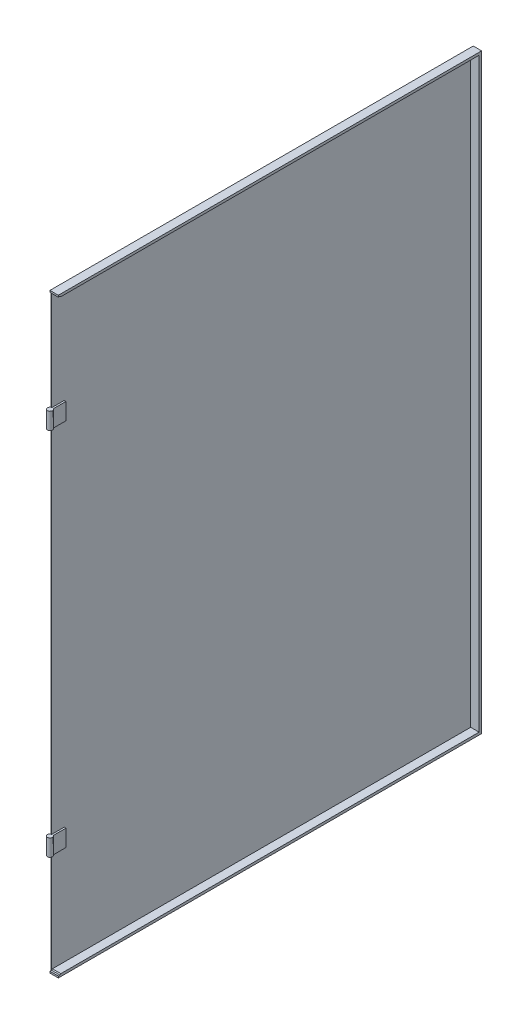
SolidWorks part; units mm, degrees
material "Acero inoxidable al cromo"
ref_plane "Alzado" through (0, 0, 0) normal (0, 0, 1) x (1, 0, 0)
ref_plane "Planta" through (0, 0, 0) normal (0, 1, 0) x (1, 0, 0)
ref_plane "Vista lateral" through (0, 0, 0) normal (1, 0, 0) x (0, 0, -1)
sketch "Croquis1" plane through (0, 0, 0) normal (0, 0, 1) x (1, 0, 0)
  line L1 (-250, -350) -> (250, -350)
  line L2 (-250, -350) -> (-250, 350)
  line L3 (-250, 350) -> (250, 350)
  line L4 (250, -350) -> (250, 350)
  line L5 (-250, -350) -> (250, 350) construction
  line L6 (-250, 350) -> (250, -350) construction
  point P0 (0, 0)
  dimension "D1" = 700
  dimension "D2" = 500
extrude "Saliente-Extruir1" add sketch "Croquis1" along normal blind 500
shell "Vaciado1" thickness 1
sketch "Croquis2" plane through (-249, 0, 0) normal (1, 0, 0) x (0, 0, -1)
  line L0 (-500, 349) -> (-500, -349) construction
  line L1 (-500, 230) -> (-485, 230)
  line L2 (-500, 230) -> (-500, 210)
  line L3 (-500, 210) -> (-485, 210)
  line L4 (-485, 230) -> (-485, 210)
  line L5 (-500, 350) -> (0, 350) construction
  line L6 (-500, -210) -> (-485, -210)
  line L7 (-500, -210) -> (-500, -230)
  line L8 (-500, -230) -> (-485, -230)
  line L9 (-485, -210) -> (-485, -230)
  line L10 (-500, -350) -> (0, -350) construction
  dimension "D1" = 20
  dimension "D2" = 15
  dimension "D3" = 20
  dimension "D4" = 15
  dimension "D5" = 120
  dimension "D6" = 120
extrude "Saliente-Extruir2" add sketch "Croquis2" along normal blind 2
sketch "Croquis3" plane through (0, -230, 0) normal (0, -1, 0) x (1, 0, 0)
  line L0 (-250, 500) -> (-250, 0) construction
  line L1 (-250, 500) -> (250, 500) construction
  circle A0 centre (-248.5, 502.5) radius 3
  dimension "D1" = 6
  dimension "D2" = 1.5
  dimension "D3" = 2.5
extrude "Saliente-Extruir3" add sketch "Croquis3" against normal up to vertex
sketch "Croquis4" plane through (0, 210, 0) normal (0, -1, 0) x (1, 0, 0)
  line L0 (-250, 499.9019) -> (-247, 499.9019)
  arc A0 (-247, 499.9019) -> (-250, 499.9019) centre (-248.5, 502.5) ccw construction
  arc A1 (-247, 499.9019) -> (-250, 499.9019) centre (-248.5, 502.5) ccw
extrude "Saliente-Extruir4" add sketch "Croquis4" against normal up to vertex contours A1 L0
sketch "Croquis5" plane through (-249, 0, 0) normal (1, 0, 0) x (0, 0, -1)
  line L12 (-485, -210) -> (-485, -230)
  line L13 (-485, -230) -> (-500, -230)
  line L14 (-500, -230) -> (-500, -349)
  line L15 (-500, -349) -> (-1, -349)
  line L16 (-1, -349) -> (-1, 349)
  line L17 (-1, 349) -> (-500, 349)
  line L18 (-500, 349) -> (-500, 230)
  line L19 (-500, 230) -> (-485, 230)
  line L20 (-485, 230) -> (-485, 210)
  line L21 (-485, 210) -> (-500, 210)
  line L22 (-500, 210) -> (-500, -210)
  line L23 (-500, -210) -> (-485, -210)
  line L24 (-485, -210) -> (-485, -230)
  line L25 (-485, -230) -> (-500, -230)
  line L26 (-500, -230) -> (-500, -349)
  line L27 (-500, -349) -> (-1, -349)
  line L28 (-1, -349) -> (-1, 349)
  line L29 (-1, 349) -> (-500, 349)
  line L30 (-500, 349) -> (-500, 230)
  line L31 (-500, 230) -> (-485, 230)
  line L32 (-485, 230) -> (-485, 210)
  line L33 (-485, 210) -> (-500, 210)
  line L34 (-500, 210) -> (-500, -210)
  line L35 (-500, -210) -> (-485, -210)
  dimension "D1" = 0
extrude "Cortar-Extruir1" cut sketch "Croquis5" along normal through all
sketch "Croquis6" plane through (250, 0, 0) normal (1, 0, 0) x (0, 0, -1)
  line L0 (-1, -349) -> (-1, 349) construction
  circle A0 centre (-1, 0) radius 797.8448
extrude "Cortar-Extruir2" cut sketch "Croquis6" against normal blind 50
sketch "Croquis7" plane through (0, -349, 0) normal (0, 1, 0) x (1, 0, 0)
  line L4 (-249, -500) -> (200, -500)
  line L5 (200, -500) -> (200, -1)
  line L6 (200, -1) -> (-249, -1)
  line L7 (-249, -1) -> (-249, -500)
  line L8 (-249, -500) -> (200, -500)
  line L9 (200, -500) -> (200, -1)
  line L10 (200, -1) -> (-249, -1)
  line L11 (-249, -1) -> (-249, -500)
  dimension "D1" = 0
extrude "Cortar-Extruir3" cut sketch "Croquis7" against normal blind 50
sketch "Croquis8" plane through (0, 0, 1) normal (0, 0, 1) x (1, 0, 0)
  line L4 (200, -350) -> (200, 349)
  line L5 (200, 349) -> (-249, 349)
  line L6 (-249, 349) -> (-249, -350)
  line L7 (-249, -350) -> (200, -350)
  line L8 (200, -350) -> (200, 349)
  line L9 (200, 349) -> (-249, 349)
  line L10 (-249, 349) -> (-249, -350)
  line L11 (-249, -350) -> (200, -350)
  dimension "D1" = 0
extrude "Cortar-Extruir4" cut sketch "Croquis8" against normal blind 50
sketch "Croquis9" plane through (0, 349, 0) normal (0, -1, 0) x (1, 0, 0)
  line L4 (-249, 500) -> (-249, 0)
  line L5 (-249, 0) -> (200, 0)
  line L6 (200, 0) -> (200, 500)
  line L7 (200, 500) -> (-249, 500)
  line L8 (-249, 500) -> (-249, 0)
  line L9 (-249, 0) -> (200, 0)
  line L10 (200, 0) -> (200, 500)
  line L11 (200, 500) -> (-249, 500)
  dimension "D1" = 0
extrude "Cortar-Extruir5" cut sketch "Croquis9" against normal blind 50
sketch "Croquis10" plane through (-249, 0, 0) normal (1, 0, 0) x (0, 0, -1)
  line L0 (2, 352) -> (-502, 352)
  line L1 (-502, 352) -> (-502, 228)
  line L2 (-502, 228) -> (-487, 228)
  line L3 (-487, 228) -> (-487, 212)
  line L4 (-487, 212) -> (-502, 212)
  line L5 (-502, 212) -> (-502, -212)
  line L6 (-502, -212) -> (-487, -212)
  line L7 (-487, -212) -> (-487, -228)
  line L8 (-487, -228) -> (-502, -228)
  line L9 (-502, -228) -> (-502, -352)
  line L10 (-502, -352) -> (2, -352)
  line L11 (2, -352) -> (2, 352)
  line L12 (-485, -210) -> (-485, -230)
  line L13 (-485, -230) -> (-500, -230)
  line L14 (-500, -230) -> (-500, -350)
  line L15 (-500, -350) -> (0, -350)
  line L16 (0, -350) -> (0, 350)
  line L17 (0, 350) -> (-500, 350)
  line L18 (-500, 350) -> (-500, 230)
  line L19 (-500, 230) -> (-485, 230)
  line L20 (-485, 230) -> (-485, 210)
  line L21 (-485, 210) -> (-500, 210)
  line L22 (-500, 210) -> (-500, -210)
  line L23 (-500, -210) -> (-485, -210)
  line L24 (-485, -210) -> (-485, -230)
  line L25 (-485, -230) -> (-500, -230)
  line L26 (-500, -230) -> (-500, -350)
  line L27 (-500, -350) -> (0, -350)
  line L28 (0, -350) -> (0, 350)
  line L29 (0, 350) -> (-500, 350)
  line L30 (-500, 350) -> (-500, 230)
  line L31 (-500, 230) -> (-485, 230)
  line L32 (-485, 230) -> (-485, 210)
  line L33 (-485, 210) -> (-500, 210)
  line L34 (-500, 210) -> (-500, -210)
  line L35 (-500, -210) -> (-485, -210)
  line L36 (-500, 350) -> (-502, 350)
  line L37 (-500, -350) -> (-502, -350)
  line L62 (-500, -350) -> (-499, -349)
  line L63 (-499, 349) -> (-500, 350)
  line L74 (-484, -209) -> (-484, -231)
  line L75 (-484, -231) -> (-499, -231)
  line L76 (-499, -231) -> (-499, -349)
  line L77 (-499, -349) -> (-1, -349)
  line L78 (-1, -349) -> (-1, 349)
  line L79 (-1, 349) -> (-499, 349)
  line L80 (-499, 349) -> (-499, 231)
  line L81 (-499, 231) -> (-484, 231)
  line L82 (-484, 231) -> (-484, 209)
  line L83 (-484, 209) -> (-499, 209)
  line L84 (-499, 209) -> (-499, -209)
  line L85 (-499, -209) -> (-484, -209)
  line L86 (-484, -209) -> (-484, -231)
  line L87 (-484, -231) -> (-499, -231)
  line L88 (-499, -231) -> (-499, -349)
  line L89 (-499, -349) -> (-1, -349)
  line L90 (-1, -349) -> (-1, 349)
  line L91 (-1, 349) -> (-499, 349)
  line L92 (-499, 349) -> (-499, 231)
  line L93 (-499, 231) -> (-484, 231)
  line L94 (-484, 231) -> (-484, 209)
  line L95 (-484, 209) -> (-499, 209)
  line L96 (-499, 209) -> (-499, -209)
  line L97 (-499, -209) -> (-484, -209)
  dimension "D3" = 1
  dimension "D1" = 0
  dimension "D2" = 2
extrude "Saliente-Extruir5" add sketch "Croquis10" along normal blind 10
